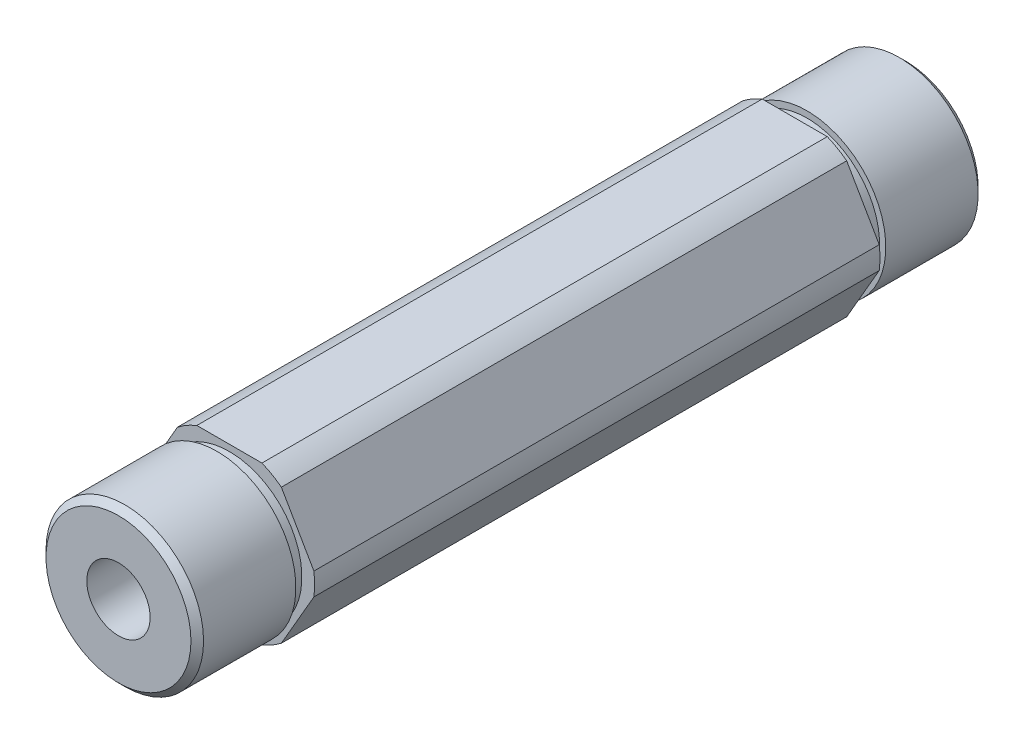
SolidWorks part; units mm, degrees
material "6061-T6 (SS)"
ref_plane "Front Plane" through (0, 0, 0) normal (0, 0, 1) x (1, 0, 0)
ref_plane "Top Plane" through (0, 0, 0) normal (0, 1, 0) x (1, 0, 0)
ref_plane "Right Plane" through (0, 0, 0) normal (1, 0, 0) x (0, 0, -1)
sketch "Sketch1" plane through (0, 0, 0) normal (1, 0, 0) x (0, 0, -1)
  line L0 (0, 0) -> (-10504.8235, 0) construction
  line L1 (0, 2.5527) -> (0, 6.35)
  line L2 (0, 6.35) -> (7.9502, 6.35)
  line L3 (7.9502, 6.35) -> (7.9502, 5.842)
  line L4 (7.9502, 5.842) -> (8.9408, 5.842)
  line L5 (8.9408, 5.842) -> (8.9408, 6.8707)
  line L6 (8.9408, 6.8707) -> (19.8857, 6.8707)
  line L7 (19.8857, 6.8707) -> (19.8857, 0) construction
  line L8 (0, 2.5527) -> (19.8857, 2.5527)
  line L9 (19.8857, 6.8707) -> (54.5084, 6.8707)
  line L10 (54.5084, 6.8707) -> (54.5084, 5.842)
  line L11 (54.5084, 5.842) -> (55.499, 5.842)
  line L12 (55.499, 5.842) -> (55.499, 6.35)
  line L13 (55.499, 6.35) -> (63.4492, 6.35)
  line L14 (63.4492, 6.35) -> (63.4492, 2.5527)
  line L15 (63.4492, 2.5527) -> (19.8857, 2.5527)
  dimension "D1" = 5.1054
  dimension "D2" = 12.7
  dimension "D3" = 11.684
  dimension "D4" = 0.9906
  dimension "D5" = 7.9502
  dimension "D6" = 47.5488
  dimension "D7" = 7.9502
  dimension "D8" = 13.7414
revolve "Revolve1" add sketch "Sketch1" angle 360 about L0
sketch "Sketch2" plane through (0, 0, -8.9408) normal (0, 0, 1) x (1, 0, 0)
  line L1 (-3.6662, 6.35) -> (-7.3323, 0)
  line L2 (-7.3323, 0) -> (-3.6662, -6.35)
  line L3 (-3.6662, -6.35) -> (3.6662, -6.35)
  line L4 (3.6662, -6.35) -> (7.3323, 0)
  line L5 (7.3323, 0) -> (3.6662, 6.35)
  line L6 (3.6662, 6.35) -> (-3.6662, 6.35)
  circle A0 centre (0, 0) radius 6.35 construction
  dimension "D1" = 12.7
extrude "Cut-Extrude1" cut sketch "Sketch2" against normal through all flip side to cut
chamfer "Chamfer1" distance 0.508 angle 45 2 edges at (-6.35, 0, -63.4492) (-6.35, 0, 0)
